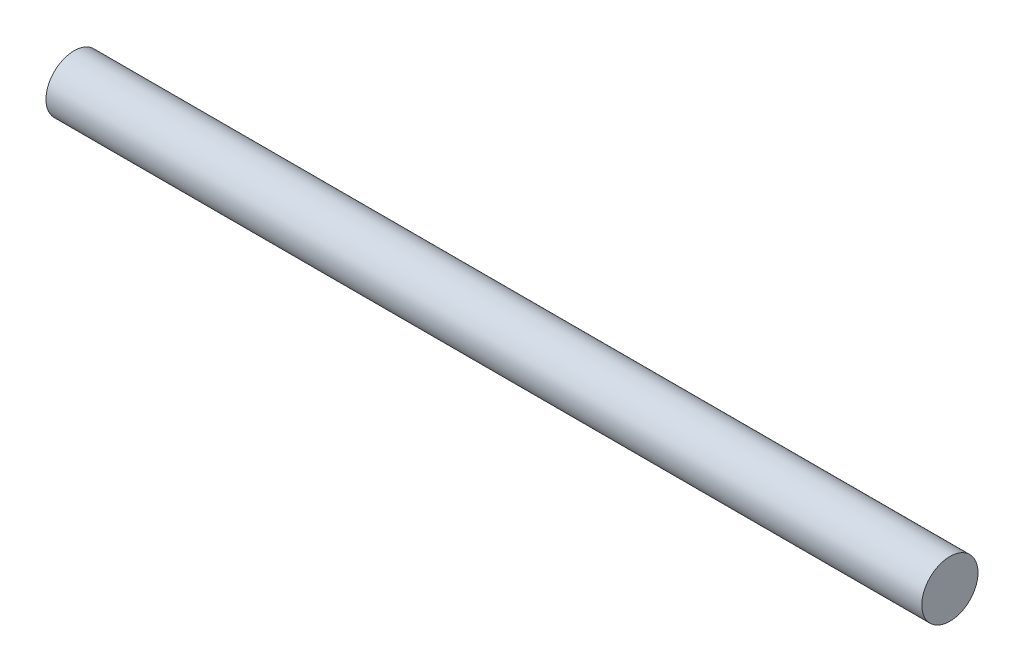
SolidWorks part; units mm, degrees
ref_plane "Front Plane" through (0, 0, 0) normal (0, 0, 1) x (1, 0, 0)
ref_plane "Top Plane" through (0, 0, 0) normal (0, 1, 0) x (1, 0, 0)
ref_plane "Right Plane" through (0, 0, 0) normal (1, 0, 0) x (0, 0, -1)
sketch "Sketch2" plane through (0, 0, 0) normal (1, 0, 0) x (0, 0, -1)
  circle A0 centre (0, 0) radius 2.5
  dimension "D1" = 5
extrude "Boss-Extrude1" add sketch "Sketch2" along normal blind 74.8
other "Move Face1" face at (74.8, 0, -2.5) parameters "D1"=0.1
